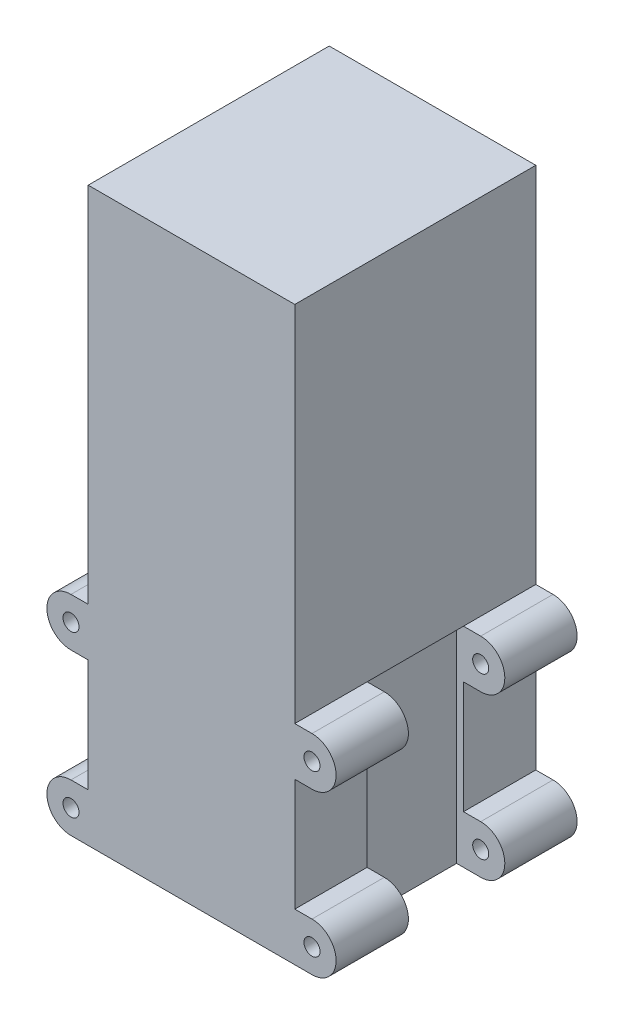
SolidWorks part; units mm, degrees
ref_plane "Спереди" through (0, 0, 0) normal (0, 0, 1) x (1, 0, 0)
ref_plane "Сверху" through (0, 0, 0) normal (0, 1, 0) x (1, 0, 0)
ref_plane "Справа" through (0, 0, 0) normal (1, 0, 0) x (0, 0, -1)
sketch "Эскиз1" plane through (0, 0, 0) normal (0, 0, 1) x (1, 0, 0)
  line L0 (-15, 65.9849) -> (-15, 3) construction
  line L1 (0, 97.0287) -> (0, 0) construction
  line L2 (-15, 20) -> (-12.8572, 20)
  line L3 (-12.8572, 20) -> (-12.8572, 6)
  line L4 (-15, 6) -> (-12.8572, 6)
  line L5 (-15, 26) -> (-12.8572, 26)
  line L6 (-15, 0) -> (0, 0)
  line L7 (0, 0) -> (0, 55.1609)
  line L8 (-12.8572, 26) -> (-12.8572, 71.185)
  line L9 (-12.8572, 71.185) -> (0, 71.185)
  line L10 (0, 71.185) -> (0, 55.1609)
  arc A0 (-15, 6) -> (-15, 0) centre (-15, 3) ccw
  arc A1 (-15, 26) -> (-15, 20) centre (-15, 23) ccw
  circle A2 centre (-15, 23) radius 1
  circle A3 centre (-15, 3) radius 1
  point P19 (0, 97.0287)
  point P20 (0, 0)
  dimension "D2" = 6
  dimension "D3" = 20
  dimension "D4" = 2
  dimension "D1" = 15
extrude "Бобышка-Вытянуть1" add sketch "Эскиз1" against normal blind 30
sketch "Эскиз2" plane through (0, 0, 0) normal (0, 1, 0) x (1, 0, 0)
  line L0 (-18, 30) -> (-18, 0) construction
  line L1 (-18, 21) -> (-12, 21)
  line L2 (-18, 21) -> (-18, 9)
  line L3 (-18, 9) -> (-12, 9)
  line L4 (-12, 21) -> (-12, 9)
  line L6 (-18, 0) -> (-15, 0) construction
  dimension "D1" = 9
  dimension "D2" = 12
  dimension "D3" = 6
extrude "Вырез-Вытянуть1" cut sketch "Эскиз2" along normal up to surface (26 mm away) contours L4 L1 L2 L3 up to face at (-13.9286, 26, -15)
mirror "Зеркальное отражение1" about plane through (0, 71.185, -30) normal (1, 0, 0) of "Вырез-Вытянуть1", "Бобышка-Вытянуть1"
